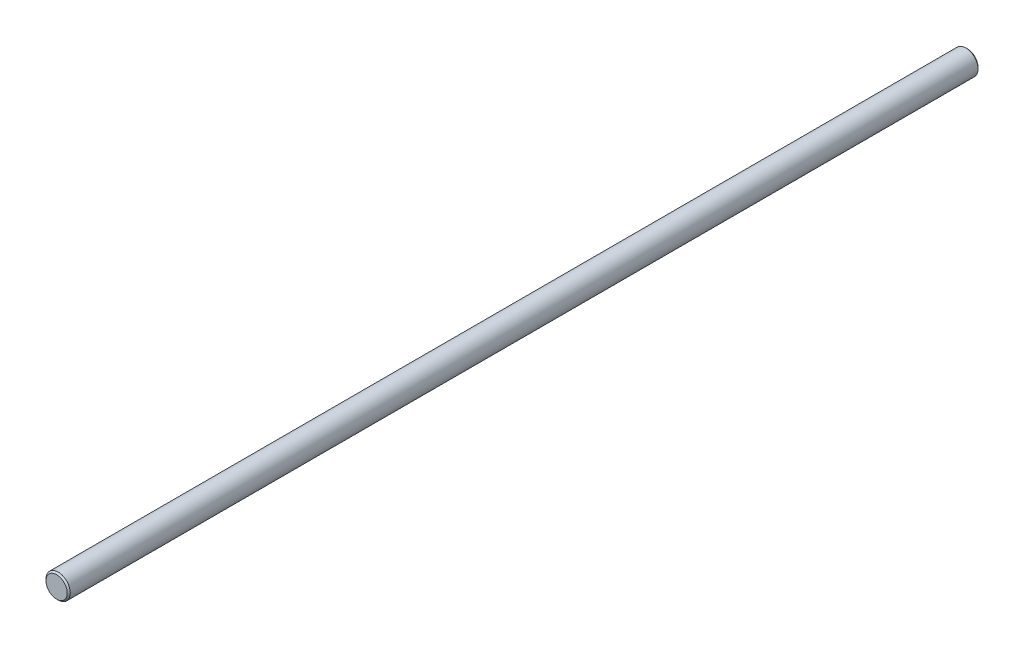
SolidWorks part; units mm, degrees
material "Plain Carbon Steel"
ref_plane "Спереди" through (0, 0, 0) normal (0, 0, 1) x (1, 0, 0)
ref_plane "Сверху" through (0, 0, 0) normal (0, 1, 0) x (1, 0, 0)
ref_plane "Справа" through (0, 0, 0) normal (1, 0, 0) x (0, 0, -1)
sketch "Sketch1" plane through (0, 0, 0) normal (0, 0, 1) x (1, 0, 0)
  circle A0 centre (0, 0) radius 4
  dimension "D1" = 8
extrude "Boss-Extrude1" add sketch "Sketch1" along normal blind 300
chamfer "Chamfer1" distance 0.5 angle 45 2 edges at (4, 0, 300) (4, 0, 0)
